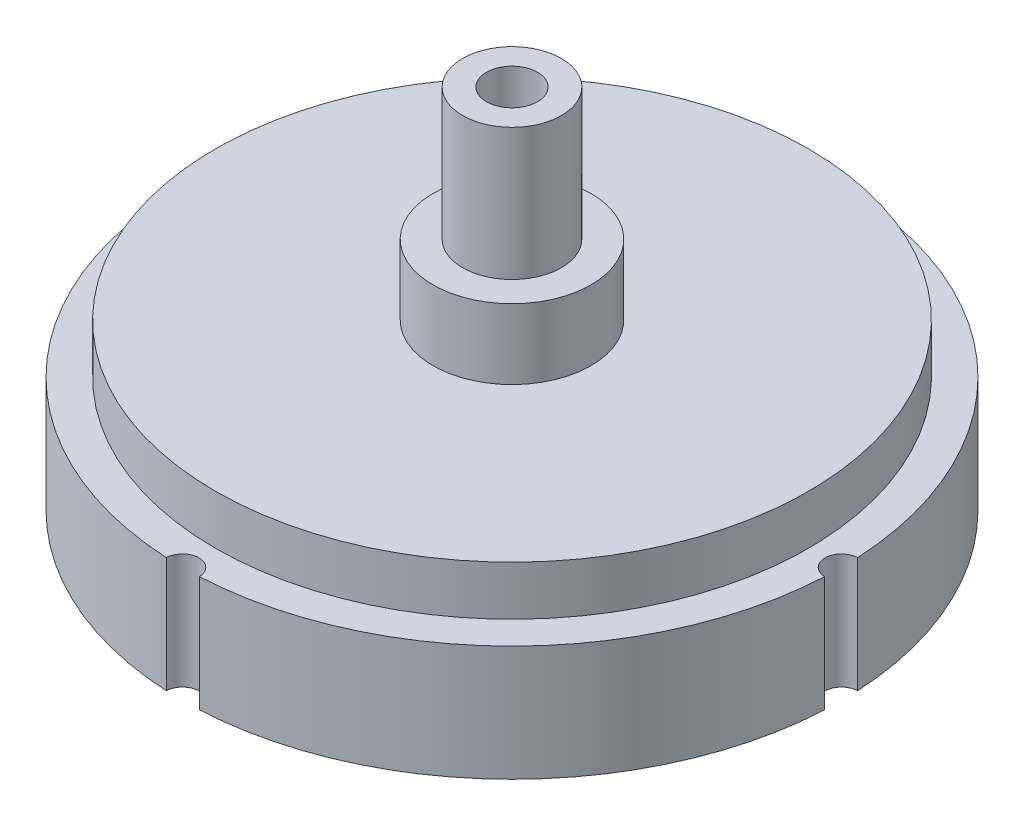
SolidWorks part; units mm, degrees
material "AISI 316 Stainless Steel Sheet (SS)"
ref_plane "Front Plane" through (0, 0, 0) normal (0, 0, 1) x (1, 0, 0)
ref_plane "Top Plane" through (0, 0, 0) normal (0, 1, 0) x (1, 0, 0)
ref_plane "Right Plane" through (0, 0, 0) normal (1, 0, 0) x (0, 0, -1)
sketch "Sketch4" plane through (0, 0, 0) normal (0, 0, 1) x (1, 0, 0)
  line L0 (0, 0) -> (0, 17.9621) construction
  line L1 (-0.775, 11.125) -> (-0.775, 4)
  line L2 (-1.2, 0) -> (-10, 0)
  line L3 (-10, 0) -> (-10, 3.5)
  line L4 (-9, 5) -> (-2.4, 5)
  line L5 (-2.4, 5) -> (-2.4, 7.125)
  line L6 (-2.4, 7.125) -> (-1.5, 7.125)
  line L7 (-1.5, 7.125) -> (-1.5, 11.125)
  line L8 (-1.5, 11.125) -> (-0.775, 11.125)
  line L9 (-10, 3.5) -> (-9, 3.5)
  line L10 (-9, 3.5) -> (-9, 5)
  line L11 (-1.2, 0) -> (-1.2, 4)
  line L12 (-1.2, 4) -> (-0.775, 4)
  dimension "D1" = 0.775
  dimension "D2" = 1.5
  dimension "D3" = 4
  dimension "D4" = 2.125
  dimension "D5" = 0.9
  dimension "D6" = 10
  dimension "D7" = 5
  dimension "D8" = 1.5
  dimension "D9" = 1
  dimension "D10" = 4
  dimension "D11" = 1.2
revolve "Revolve1" add sketch "Sketch4" angle 360 about L0
sketch "Sketch5" plane through (0, 0, 0) normal (0, -1, 0) x (1, 0, 0)
  circle A0 centre (0, 10) radius 0.5
  circle A1 centre (0, 0) radius 10 construction
  circle A2 centre (10, 0) radius 0.5
  circle A3 centre (0, -10) radius 0.5
  circle A4 centre (-10, 0) radius 0.5
  point P10 (0, 0)
  point P12 (-10, 0)
  point P13 (0, 10)
  point P14 (10, 0)
  point P15 (0, -10)
  point P16 (0, -10)
  point P17 (0, 0)
  point P18 (0, 0)
  dimension "D1" = 1
extrude "Cut-Extrude1" cut sketch "Sketch5" against normal through all both and the other way through all
